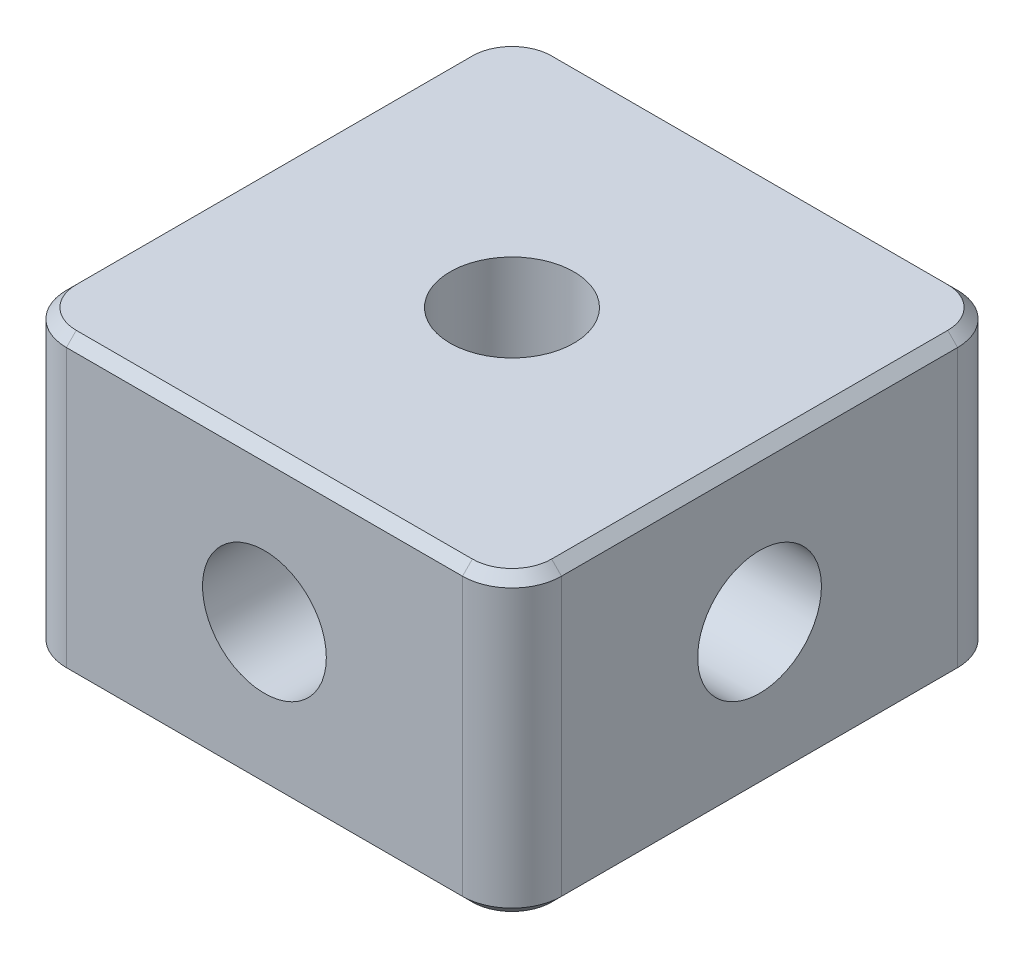
SolidWorks part; units mm, degrees
material "6061 合金"
ref_plane "前视基准面" through (0, 0, 0) normal (0, 0, 1) x (1, 0, 0)
ref_plane "上视基准面" through (0, 0, 0) normal (0, 1, 0) x (1, 0, 0)
ref_plane "右视基准面" through (0, 0, 0) normal (1, 0, 0) x (0, 0, -1)
sketch "草图1" plane through (0, 0, 0) normal (0, 1, 0) x (1, 0, 0)
  line L1 (-5, -5) -> (5, -5)
  line L2 (-5, -5) -> (-5, 5)
  line L3 (-5, 5) -> (5, 5)
  line L4 (5, -5) -> (5, 5)
  line L5 (0, 5) -> (0, -5) construction
  line L6 (-5, 0) -> (5, 0) construction
  point P0 (0, 0)
  dimension "D1" = 10
extrude "凸台-拉伸1" add sketch "草图1" along normal mid plane 6
hole_wizard "M3 螺纹孔1" positions "草图2" profile "草图3" tap size "M3" standard "GB" end condition through all
sketch "草图2" plane through (0, 3, 0) normal (0, 1, 0) x (1, 0, 0)
  point P0 (0, 0)
sketch "草图3" plane through (0, 3, 0) normal (1, 0, 0) x (0, 0, 1)
  line L0 (0, 0) -> (0, 6)
  line L1 (0, 6) -> (1.25, 6)
  line L2 (1.25, 6) -> (1.25, 0)
  line L5 (1.25, 0) -> (0, 0)
  line L11 (0, -6.35) -> (0, 107.95) construction
  dimension "通孔螺纹孔钻头直径" = 2.5
  dimension "通孔螺纹孔钻头深度" = 6
cosmetic thread "孔螺蚊线1" parameters "D2"=3
hole_wizard "M3 螺纹孔2" positions "草图4" profile "草图5" tap size "M3" standard "GB" end condition through all
sketch "草图4" plane through (0, 0, 5) normal (0, 0, 1) x (1, 0, 0)
  point P0 (0, 0)
sketch "草图5" plane through (0, 0, 5) normal (1, 0, 0) x (0, -1, 0)
  line L0 (0, 0) -> (0, 10)
  line L1 (0, 10) -> (1.25, 10)
  line L2 (1.25, 10) -> (1.25, 0)
  line L5 (1.25, 0) -> (0, 0)
  line L11 (0, -6.35) -> (0, 107.95) construction
  dimension "通孔螺纹孔钻头直径" = 2.5
  dimension "通孔螺纹孔钻头深度" = 10
cosmetic thread "孔螺蚊线2" parameters "D2"=3
hole_wizard "M3 螺纹孔3" positions "草图6" profile "草图7" tap size "M3" standard "GB" end condition through all
sketch "草图6" plane through (5, 0, 0) normal (1, 0, 0) x (0, 0, -1)
  point P0 (0, 0)
sketch "草图7" plane through (5, 0, 0) normal (0, 1, 0) x (0, 0, -1)
  line L0 (0, 0) -> (0, 10)
  line L1 (0, 10) -> (1.25, 10)
  line L2 (1.25, 10) -> (1.25, 0)
  line L5 (1.25, 0) -> (0, 0)
  line L11 (0, -6.35) -> (0, 107.95) construction
  dimension "通孔螺纹孔钻头直径" = 2.5
  dimension "通孔螺纹孔钻头深度" = 10
cosmetic thread "孔螺蚊线3" parameters "D2"=3
fillet "圆角1" radius 1 4 edges at (5, 0, -5) (5, 0, 5) (-5, 0, 5) (-5, 0, -5)
chamfer "倒角1" distance 0.2 angle 45 16 edges at (5, -3, 0) (4.7071, -3, -4.7071) (4.7071, -3, 4.7071) (0, -3, -5) (0, -3, 5) (-4.7071, -3, -4.7071) (-4.7071, -3, 4.7071) (-5, -3, 0) (5, 3, 0) (4.7071, 3, -4.7071) (4.7071, 3, 4.7071) (0, 3, -5) (0, 3, 5) (-4.7071, 3, -4.7071) (-4.7071, 3, 4.7071) (-5, 3, 0)
